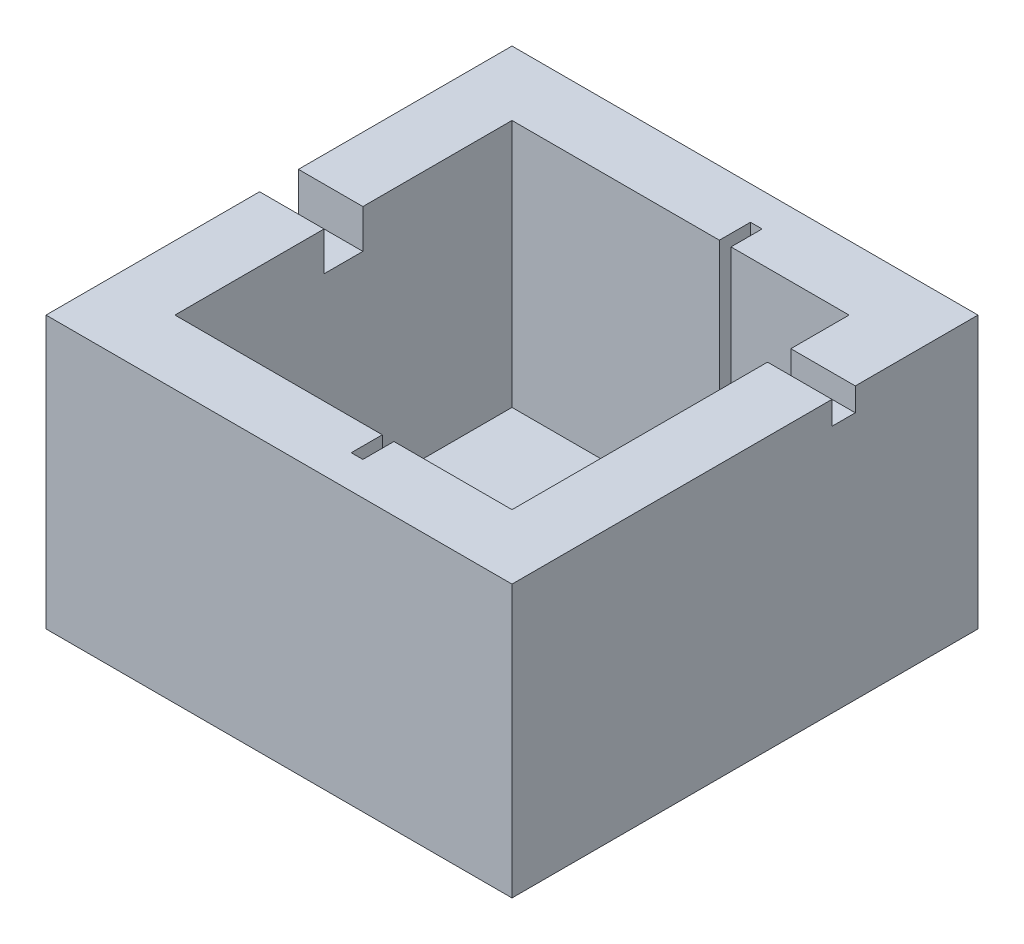
SolidWorks part; units mm, degrees
ref_plane "Front Plane" through (0, 0, 0) normal (0, 0, 1) x (1, 0, 0)
ref_plane "Top Plane" through (0, 0, 0) normal (0, 1, 0) x (1, 0, 0)
ref_plane "Right Plane" through (0, 0, 0) normal (1, 0, 0) x (0, 0, -1)
sketch "Sketch1" plane through (0, 0, 0) normal (0, 1, 0) x (1, 0, 0)
  line L1 (-34.2654, 18.6967) -> (25.7346, 18.6967)
  line L2 (-34.2654, 18.6967) -> (-34.2654, -41.3033)
  line L3 (-34.2654, -41.3033) -> (25.7346, -41.3033)
  line L4 (25.7346, 18.6967) -> (25.7346, -41.3033)
extrude "Boss-Extrude1" add sketch "Sketch1" along normal blind 35 contours L2 L1 L4 L3
sketch "Sketch2" plane through (0, 35, 0) normal (0, 1, 0) x (1, 0, 0)
  line L3 (-25.9654, 10.3967) -> (17.4346, 10.3967)
  line L4 (17.4346, 10.3967) -> (17.4346, -33.0033)
  line L5 (17.4346, -33.0033) -> (-25.9654, -33.0033)
  line L6 (-25.9654, -33.0033) -> (-25.9654, 10.3967)
extrude "Cut-Extrude1" cut sketch "Sketch2" against normal blind 32 contours L3 L4 L5 L6
sketch "Sketch3" plane through (0, 3, 0) normal (0, 1, 0) x (1, 0, 0)
  line L4 (-25.9654, 10.3967) -> (17.4346, 10.3967) construction
  line L5 (0.7346, 10.3967) -> (0.7346, 14.3967)
  line L6 (0.7346, 14.3967) -> (2.2346, 14.3967)
  line L7 (2.2346, 14.3967) -> (2.2346, 10.3967)
  line L8 (-25.9654, 10.3967) -> (17.4346, 10.3967) construction
  line L9 (2.2346, 10.3967) -> (0.7346, 10.3967)
  line L12 (17.4346, -33.0033) -> (-25.9654, -33.0033) construction
  line L13 (0.7346, -33.0033) -> (2.2346, -33.0033)
  line L14 (2.2346, -33.0033) -> (2.2346, -37.0033)
  line L15 (2.2346, -37.0033) -> (0.7346, -37.0033)
  line L16 (0.7346, -37.0033) -> (0.7346, -33.0033)
extrude "Cut-Extrude4" cut sketch "Sketch3" along normal blind 32
sketch "Sketch7" plane through (-34.2654, 0, 0) normal (-1, 0, 0) x (0, 0, 1)
  line L10 (-6.9967, 29) -> (-6.9967, 32.5)
  line L11 (-6.9967, 32.5) -> (-3.4967, 32.5)
  line L12 (-3.4967, 32.5) -> (-3.4967, 29)
  line L13 (-3.4967, 29) -> (-6.9967, 29)
extrude "Cut-Extrude7" cut sketch "Sketch7" against normal blind 76
sketch "Sketch9" plane through (25.7346, 0, 0) normal (1, 0, 0) x (0, 0, -1)
  line L1 (3.4967, 33.4084) -> (7.3811, 33.4084)
  line L2 (7.3811, 33.4084) -> (7.3811, 28.3414)
  line L3 (7.3811, 28.3414) -> (2.7855, 28.3414)
  line L4 (2.7855, 28.3414) -> (2.7855, 33.4084)
  line L5 (2.7855, 33.4084) -> (3.4967, 33.4084)
extrude "Boss-Extrude4" add sketch "Sketch9" against normal blind 8.3
sketch "Sketch12" plane through (-34.2654, 0, 0) normal (-1, 0, 0) x (0, 0, 1)
  line L1 (-6.9967, 33.5397) -> (-3.3117, 33.5397)
  line L2 (-3.3117, 33.5397) -> (-3.3117, 28.4396)
  line L3 (-3.3117, 28.4396) -> (-8.3883, 28.4396)
  line L4 (-8.3883, 28.4396) -> (-8.3883, 33.5397)
  line L5 (-8.3883, 33.5397) -> (-6.9967, 33.5397)
extrude "Boss-Extrude5" add sketch "Sketch12" against normal blind 8.3
sketch "Sketch13" plane through (25.7346, 0, 0) normal (1, 0, 0) x (0, 0, -1)
  line L10 (2.8967, 30.8) -> (2.8967, 33.8)
  line L11 (2.8967, 33.8) -> (-0.1033, 33.8)
  line L12 (-0.1033, 33.8) -> (-0.1033, 30.8)
  line L13 (-0.1033, 30.8) -> (2.8967, 30.8)
extrude "Cut-Extrude8" cut sketch "Sketch13" against normal blind 8.3
sketch "Sketch15" plane through (25.7346, 0, 0) normal (1, 0, 0) x (0, 0, -1)
  line L0 (-0.1033, 33.8) -> (-0.1033, 35)
  line L1 (18.6967, 35) -> (-41.3033, 35) construction
  line L2 (-0.1033, 35) -> (2.8967, 35)
  line L3 (2.8967, 35) -> (2.8967, 33.8)
  line L4 (2.8967, 33.8) -> (-0.1033, 33.8) construction
  line L5 (2.8967, 33.8) -> (-0.1033, 33.8)
extrude "Cut-Extrude9" cut sketch "Sketch15" against normal blind 10
sketch "Sketch18" plane through (0, 30.8, 0) normal (0, 1, 0) x (1, 0, 0)
  line L0 (25.7346, -0.1033) -> (17.4346, -0.1033)
  line L1 (17.4346, -0.1033) -> (25.7346, -0.1033) construction
  line L2 (25.7346, -0.1033) -> (25.7346, 2.8967) construction
  line L3 (17.4346, -0.1033) -> (17.4346, 2.8967) construction
  line L4 (17.4346, -0.1033) -> (17.4346, 2.8967)
  line L5 (17.4346, 2.8967) -> (25.7346, 2.8967)
  line L6 (25.7346, 2.8967) -> (25.7346, -0.1033)
extrude "Boss-Extrude7" add sketch "Sketch18" along normal blind 1.2
sketch "Sketch19" plane through (-34.2654, 0, 0) normal (-1, 0, 0) x (0, 0, 1)
  line L1 (8.8033, 35) -> (8.8033, 30)
  line L2 (8.8033, 30) -> (13.8033, 30)
  line L3 (13.8033, 30) -> (13.8033, 35)
  line L4 (-18.6967, 35) -> (41.3033, 35) construction
  line L5 (13.8033, 35) -> (8.8033, 35)
extrude "Cut-Extrude10" cut sketch "Sketch19" against normal blind 11.2 contours L1 L2 L3 L5
